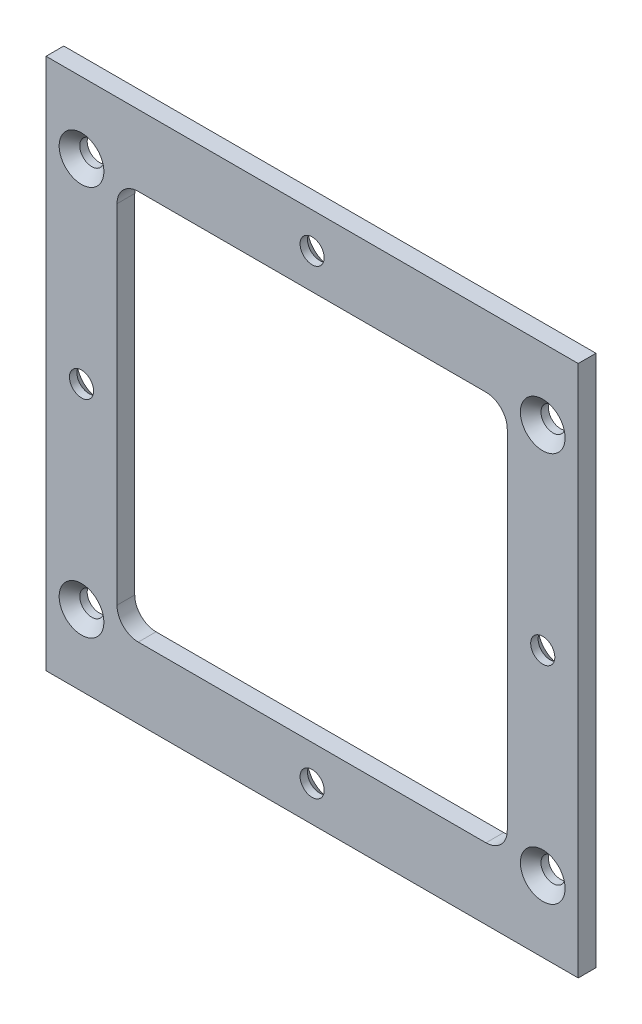
SolidWorks part; units mm, degrees
material "1060 Alloy"
ref_plane "Front Plane" through (0, 0, 0) normal (0, 0, 1) x (1, 0, 0)
ref_plane "Top Plane" through (0, 0, 0) normal (0, 1, 0) x (1, 0, 0)
ref_plane "Right Plane" through (0, 0, 0) normal (1, 0, 0) x (0, 0, -1)
sketch "Sketch1" plane through (0, 0, 0) normal (0, 0, 1) x (1, 0, 0)
  line L0 (37.5, 37.5) -> (-37.5, 37.5) construction
  line L1 (37.5, 0) -> (-37.5, 0)
  line L2 (37.5, 0) -> (37.5, 75)
  line L3 (37.5, 75) -> (-37.5, 75)
  line L4 (-37.5, 0) -> (-37.5, 75)
  line L5 (0, 0) -> (0, 75) construction
  line L7 (-24.5, 10) -> (24.5, 10)
  line L8 (-27.5, 13) -> (-27.5, 62)
  line L9 (-24.5, 65) -> (24.5, 65)
  line L10 (27.5, 13) -> (27.5, 62)
  line L11 (-27.5, 10) -> (27.5, 65) construction
  line L12 (-27.5, 65) -> (27.5, 10) construction
  arc A0 (-27.5, 62) -> (-24.5, 65) centre (-24.5, 62) cw
  arc A1 (24.5, 65) -> (27.5, 62) centre (24.5, 62) cw
  arc A2 (24.5, 10) -> (27.5, 13) centre (24.5, 13) ccw
  arc A3 (-24.5, 10) -> (-27.5, 13) centre (-24.5, 13) cw
  point P11 (0, 37.5)
  dimension "D2" = 3
  dimension "D3" = 3
  dimension "D1" = 10
extrude "Boss-Extrude1" add sketch "Sketch1" along normal blind 2.5
hole_wizard "CSK for M3 Oval Head Machine Screw1" positions "3DSketch1" profile "Sketch2" countersink size "M3" standard "Ansi Metric" end condition through all
sketch3d "3DSketch1"
  line L0 (-37.5, 0, 2.5) -> (37.5, 0, 2.5) construction
  line L1 (37.5, 75, 2.5) -> (-37.5, 75, 2.5) construction
  line L2 (37.5, 0, 2.5) -> (37.5, 75, 2.5) construction
  line L3 (-37.5, 75, 2.5) -> (-37.5, 0, 2.5) construction
  point P0 (32.5, 10, 2.5)
  point P2 (-32.5, 10, 2.5)
  point P4 (-32.5, 65, 2.5)
  point P6 (32.5, 65, 2.5)
  dimension "D1" = 10
  dimension "D2" = 10
  dimension "D3" = 5
  dimension "D4" = 5
sketch "Sketch2" plane through (32.5, 10, 2.5) normal (1, 0, 0) x (0, -1, 0)
  line L0 (0, 0) -> (0, 2.5)
  line L1 (0, 2.5) -> (1.7, 2.5)
  line L2 (1.7, 2.5) -> (1.7, 1.45)
  line L3 (1.7, 1.45) -> (3.15, 0)
  line L5 (3.15, 0) -> (0, 0)
  line L6 (-1.7, 1.45) -> (-3.15, 0) construction
  line L11 (0, -6.35) -> (0, 107.95) construction
  dimension "Thru Hole Dia." = 3.4
  dimension "Thru Hole Depth" = 2.5
  dimension "Near C'Sink Dia." = 6.3
  dimension "Near C'Sink Angle" = 90
hole_wizard "CSK for M3 Oval Head Machine Screw2" positions "Sketch4" profile "Sketch3" countersink size "M3" standard "Ansi Metric" end condition through all
sketch "Sketch4" plane through (0, 0, 0) normal (0, 0, -1) x (-1, 0, 0)
  line L8 (0, 0) -> (0, 10) construction
  line L9 (24.5, 10) -> (-24.5, 10) construction
  line L11 (-27.5, 37.5) -> (-37.5, 37.5) construction
  line L12 (-27.5, 13) -> (-27.5, 62) construction
  line L13 (-37.5, 0) -> (-37.5, 75) construction
  line L15 (37.5, 37.5) -> (27.5, 37.5) construction
  line L16 (37.5, 75) -> (37.5, 0) construction
  line L17 (27.5, 62) -> (27.5, 13) construction
  line L19 (0, 65) -> (0, 75) construction
  line L20 (-24.5, 65) -> (24.5, 65) construction
  line L21 (-37.5, 75) -> (37.5, 75) construction
  point P53 (0, 5)
  point P55 (32.5, 37.5)
  point P57 (-32.5, 37.5)
  point P59 (0, 70)
sketch "Sketch3" plane through (0, 5, 0) normal (1, 0, 0) x (0, 1, 0)
  line L0 (0, 0) -> (0, 2.5)
  line L1 (0, 2.5) -> (1.7, 2.5)
  line L2 (1.7, 2.5) -> (1.7, 1.45)
  line L3 (1.7, 1.45) -> (3.15, 0)
  line L5 (3.15, 0) -> (0, 0)
  line L6 (-1.7, 1.45) -> (-3.15, 0) construction
  line L11 (0, -6.35) -> (0, 107.95) construction
  dimension "Thru Hole Dia." = 3.4
  dimension "Thru Hole Depth" = 2.5
  dimension "Near C'Sink Dia." = 6.3
  dimension "Near C'Sink Angle" = 90
